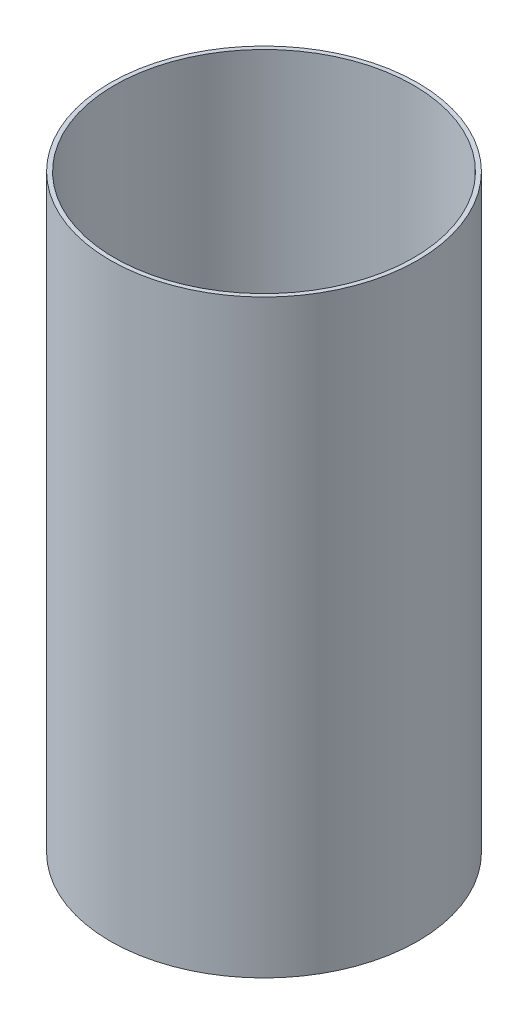
SolidWorks part; units mm, degrees
material "Silica Phenolic"
ref_plane "Piano frontale" through (0, 0, 0) normal (0, 0, 1) x (1, 0, 0)
ref_plane "Piano superiore" through (0, 0, 0) normal (0, 1, 0) x (1, 0, 0)
ref_plane "Piano destro" through (0, 0, 0) normal (1, 0, 0) x (0, 0, -1)
sketch "Schizzo1" plane through (0, 0, 0) normal (0, 0, 1) x (1, 0, 0)
  line L0 (0, 0) -> (0, 21.1255) construction
  line L1 (-72, 0) -> (-72, 3)
  line L2 (-72, 3) -> (-71, 3)
  line L3 (-71, 3) -> (-71, 280)
  line L7 (-73, 280) -> (-73, 0)
  line L8 (-73, 0) -> (-72, 0)
  line L9 (-71, 280) -> (-73, 280)
  point P7 (-72.9608, 280.0426)
  point P8 (-71, 280.2166)
  dimension "D1" = 2
  dimension "D2" = 142
  dimension "D3" = 3
  dimension "D4" = 280
revolve "Rivoluzione1" add sketch "Schizzo1" angle 360 about L0
